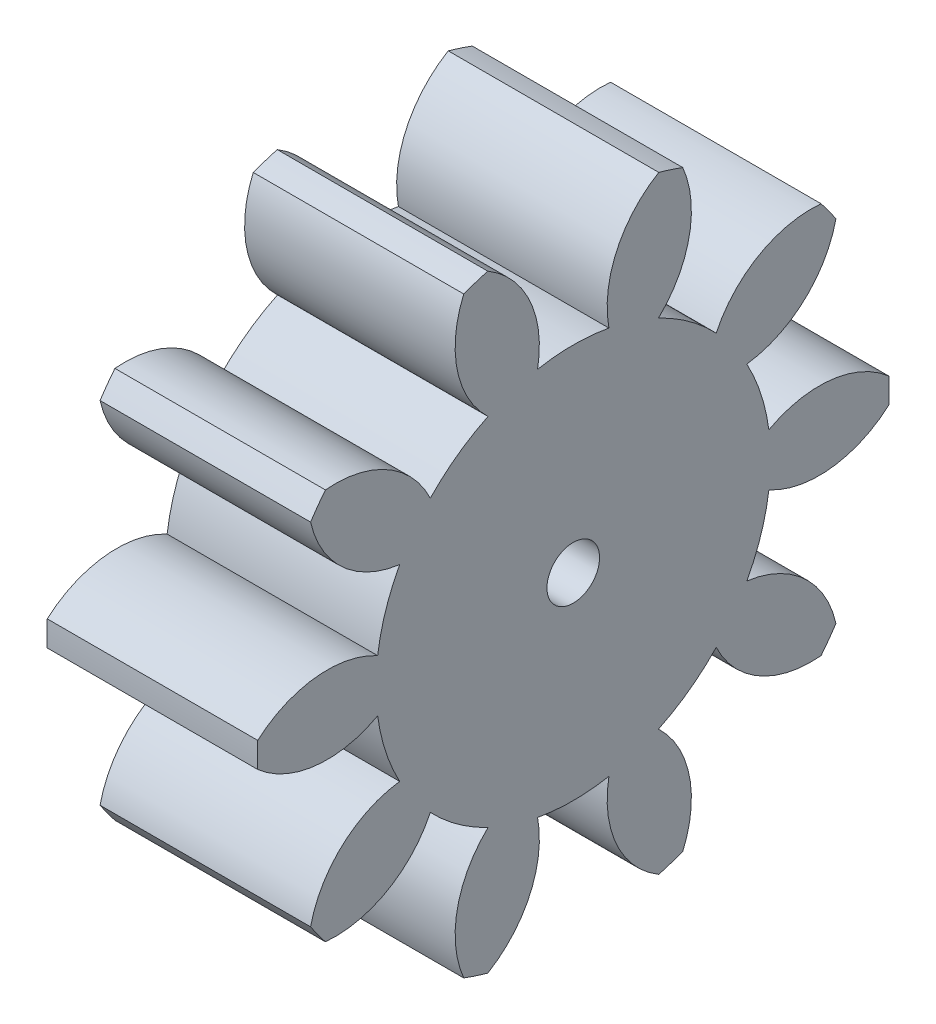
SolidWorks part; units mm, degrees
ref_plane "Plane1" through (0, 0, 0) normal (0, 0, 1) x (1, 0, 0)
ref_plane "Plane2" through (0, 0, 0) normal (0, 1, 0) x (1, 0, 0)
ref_plane "Plane3" through (0, 0, 0) normal (1, 0, 0) x (0, 0, -1)
sketch "HoldingSke" plane through (0, 0, 0) normal (0, 1, 0) x (1, 0, 0)
  line L0 (0, 0) -> (0.3283, -0.0579)
  line L1 (-15, 0) -> (100, 0) construction
  line L2 (0, 0) -> (-2.1039, 2.3779)
  line L3 (0, 0) -> (-11.863, 4.5341)
  line L4 (0, 0) -> (8.5048, 1.4996)
  line L5 (0, 0) -> (-46.8476, -17.4728)
  line L6 (0, 0) -> (-9.9476, -6.7116)
  line L7 (-2.1039, 2.3779) -> (8.6586, 51.2059)
  line L8 (-76.2, 54.61) -> (-75.7, 54.61)
  line L9 (-67.7845, 28.3722) -> (-49.3413, 33.142)
  line L10 (-76.2, 71.12) -> (104.1128, 71.12)
  line L11 (0, 0) -> (-12, 0)
  line L12 (-76.2, 101.6) -> (-76.093, 101.6)
  line L13 (24.9733, 27.94) -> (52.9518, 28.4284)
  line L14 (24.9733, 27.94) -> (24.9743, 27.94)
  line L15 (24.9733, 27.94) -> (100.4006, 29.5858)
  line L16 (-63.627, -3) -> (-12.827, -3)
  circle A0 centre (0, 0) radius 1.5
  circle A1 centre (0, 0) radius 11.249
  circle A2 centre (0, 0) radius 37.5
  circle A3 centre (0, 0) radius 1.5
  dimension "MHD" = 22.498
  dimension "Hub_dia" = 75
  dimension "Bore" = 3
  dimension "MBD" = 3
  dimension "Num_teeth" = 10
  dimension "Pitch" = 0.3333
  dimension "Overall_len" = 50
  dimension "Show_teeth" = 10
  dimension "Thickness" = 12
  dimension "OAL" = 50.0001
  dimension "T_dim" = 0.5
  dimension "Ap" = 14.5
  dimension "H" = 19.05
  dimension "Pitch_radius" = 180.3128
  dimension "Width" = 12
  dimension "Backlash" = 0.107
  dimension "Addendum_fac" = 1
  dimension "Dedendum_fac" = 1.25
  dimension "Clearance_fac" = 0.25
  dimension "Dedendum_add" = 0.001
  dimension "Module" = 3
sketch "BasProSke" plane through (0, 0, 0) normal (0, 1, 0) x (1, 0, 0)
  line L0 (-10, 0) -> (60, 0) construction
  line L1 (0, 0) -> (0, 18)
  line L2 (0, 0) -> (12, 0)
  line L3 (12, 0) -> (12, 18)
  line L4 (12, 18) -> (0, 18)
  dimension "Thickness" = 12
  dimension "Diameter" = 36
revolve "Base-Revolve" add sketch "BasProSke" angle 360 about L0
sketch "TooCutSke" plane through (0, 0, 0) normal (1, 0, 0) x (0, 0, -1)
  line L1 (0, 0) -> (0, 107) construction
  line L2 (0, 0) -> (-2.5334, 14.7845) construction
  line L3 (0, 0) -> (-9.174, 28.2345) construction
  line L4 (-2.5334, 14.7845) -> (-4.587, 14.1173) construction
  arc A0 (2.0333, 11.0637) -> (-2.0333, 11.0637) centre (0, 0) ccw
  arc A1 (4.9042, 17.3454) -> (-4.9042, 17.3454) centre (0, 0) ccw
  circle A2 centre (0, 0) radius 15 construction
  circle A3 centre (0, 0) radius 14.5222 construction
  arc A4 (-2.0333, 11.0637) -> (-4.9042, 17.3454) centre (-7.9314, 12.165) ccw
  arc A5 (4.9042, 17.3454) -> (2.0333, 11.0637) centre (7.9314, 12.165) ccw
  dimension "Root_dia" = 22.498
  dimension "Overcut_dia" = 36.0508
  dimension "Pitch_dia" = 30
  dimension "Base_dia" = 29.0444
  dimension "Flank_rad" = 6
  dimension "Half_ang" = 18
  dimension "Half_CT" = 2.1593
extrude "ToothCut" cut sketch "TooCutSke" along normal through all
fillet "Breaks" [suppressed] radius 0.06
fillet "RootFillets" [suppressed] radius 0.751
pattern_circular "TeethCuts" count 10 every 36 about axis through (-10, 0, 0) along (1, 0, 0) of "ToothCut", "RootFillets", "Breaks"
sketch "HubNeaOneSke" plane through (0, 0, 0) normal (-1, 0, 0) x (0, 0, 1)
  circle A0 centre (0, 0) radius 11.249
  dimension "Diameter" = 22.498
extrude "HubNearOne" [suppressed] add sketch "HubNeaOneSke" along normal blind 38.0001
sketch "HubNeaBotSke" plane through (0, 0, 0) normal (-1, 0, 0) x (0, 0, 1)
  circle A0 centre (0, 0) radius 11.249
  dimension "Diameter" = 22.498
extrude "HubNearBoth" [suppressed] add sketch "HubNeaBotSke" along normal blind 19
ref_plane "FarPln" through (12, 0, 0) normal (1, 0, 0) x (0, 0, -1)
sketch "HubFarSke" plane through (12, 0, 0) normal (1, 0, 0) x (0, 0, -1)
  circle A0 centre (0, 0) radius 11.249
  dimension "Diameter" = 22.498
extrude "HubFar" [suppressed] add sketch "HubFarSke" along normal blind 19
sketch "BorSke" plane through (0, 0, 0) normal (1, 0, 0) x (0, 0, -1)
  circle A0 centre (0, 0) radius 1.5
  dimension "Diameter" = 3
extrude "Bore" cut sketch "BorSke" along normal mid plane 100.0001
sketch "KeySke" plane through (0, 0, 0) normal (1, 0, 0) x (0, 0, -1)
  line L0 (-0.6, 0) -> (-0.6, 2)
  line L1 (-0.6, 2) -> (0.6, 2)
  line L2 (0.6, 2) -> (0.6, 0)
  line L3 (0, 0) -> (0, 34) construction
  line L4 (-0.6, 0) -> (0.6, 0)
  dimension "Offset" = 2
extrude "Keyway" [suppressed] cut sketch "KeySke" along normal mid plane 100.0001
pattern_circular "Keyway2" [suppressed] count 2 every 90 about axis through (-10, 0, 0) along (1, 0, 0)
equation "' \"Module@HoldingSke\" = 6.35"
equation "' \"Num_teeth@HoldingSke\" = 12"
equation "' \"Ap@HoldingSke\" =  20"
equation "' \"Ap@HoldingSke\" = 20"
equation "' \"Width@HoldingSke\" = 0.5 * 25.4"
equation "' \"Hub_dia@HoldingSke\"= 1 * 25.4"
equation "' \"Hub_dia@HoldingSke\" = 1 * 25.4"
equation "' \"Overall_len@HoldingSke\" = 1.0 * 25.4"
equation "' \"Bore@HoldingSke\" = 0.75 * 25.4"
equation "' \"T_dim@HoldingSke\" = 0.1 * 25.4"
equation "' \"Width@KeySke\" = 0.25 * 25.4"
equation "' \"Show_teeth@HoldingSke\" = 13"
equation "' \"Backlash@HoldingSke\" = 0.009 * 25.4"
equation "' \"Addendum_fac@HoldingSke\" = 1.0"
equation "' \"Dedendum_fac@HoldingSke\" = 1.25"
equation "' \"Dedendum_add@HoldingSke\" = 0.00005 * 25.4"
equation "' \"Clearance_fac@HoldingSke\" = 0.25"
equation "\"Pitch@HoldingSke\" = 1 / \"Module@HoldingSke\""
equation "\"Overcut_dia@TooCutSke\" = (\"Num_teeth@HoldingSke\" + 2 * \"Addendum_fac@HoldingSke\") / \"Pitch@HoldingSke\" + 0.002 * 25.4"
equation "\"Pitch_dia@TooCutSke\" = \"Num_teeth@HoldingSke\" / \"Pitch@HoldingSke\""
equation "\"Base_dia@TooCutSke\" = \"Num_teeth@HoldingSke\" / \"Pitch@HoldingSke\" * cos((\"Ap@HoldingSke\"  * 3.14159265 / 180))"
equation "\"Root_dia@TooCutSke\" = (\"Num_teeth@HoldingSke\" + 2) / \"Pitch@HoldingSke\" - 2 * (\"Addendum_fac@HoldingSke\" + \"Dedendum_fac@HoldingSke\") / \"Pitch@HoldingSke\" - \"Dedendum_add@HoldingSke\" * 2"
equation "\"Half_ang@TooCutSke\" = 180 / \"Num_teeth@HoldingSke\""
equation "\"Half_CT@TooCutSke\" = \"Num_teeth@HoldingSke\" / \"Pitch@HoldingSke\" * sin((3.14159265 / 2 / \"Num_teeth@HoldingSke\")) / 2 - 7 * \"Backlash@HoldingSke\" / 4"
equation "\"Flank_rad@TooCutSke\" = \"Num_teeth@HoldingSke\" / \"Pitch@HoldingSke\" / 5"
equation "\"Radius@RootFillets\" = \"Clearance_fac@HoldingSke\" / \"Pitch@HoldingSke\" + \"Dedendum_add@HoldingSke\""
equation "\"Break_rad@Breaks\" = 0.02 / \"Pitch@HoldingSke\""
equation "\"Thickness@HoldingSke\" = \"Width@HoldingSke\""
equation "\"OAL@HoldingSke\" = \"Thickness@HoldingSke\""
equation "\"MHD@HoldingSke\" = (\"Num_teeth@HoldingSke\" + 2) / \"Pitch@HoldingSke\" - 2 * (\"Addendum_fac@HoldingSke\" + \"Dedendum_fac@HoldingSke\")  / \"Pitch@HoldingSke\" - \"Dedendum_add@HoldingSke\" * 2"
equation "\"MBD@HoldingSke\" = (\"Num_teeth@HoldingSke\" + 2) / \"Pitch@HoldingSke\" - 2 * (\"Addendum_fac@HoldingSke\" + \"Dedendum_fac@HoldingSke\")  / \"Pitch@HoldingSke\" - \"Dedendum_add@HoldingSke\" * 2 - 0.002 * 25.4"
equation "\"MHD@HoldingSke\" = ((sgn( \"MHD@HoldingSke\" - \"Hub_dia@HoldingSke\" )-1)*( \"MHD@HoldingSke\" - \"Hub_dia@HoldingSke\" ))/-2+ \"Hub_dia@HoldingSke\""
equation "\"MBD@HoldingSke\" = ((sgn( \"MBD@HoldingSke\" - \"Bore@HoldingSke\" )-1)*( \"MBD@HoldingSke\" - \"Bore@HoldingSke\" ))/-2+ \"Bore@HoldingSke\""
equation "\"OAL@HoldingSke\" = ((sgn( \"OAL@HoldingSke\" - \"Overall_len@HoldingSke\" )+1)*( \"OAL@HoldingSke\" - \"Overall_len@HoldingSke\" ))/2 + \"Overall_len@HoldingSke\" + 0.000002 * 25.4"
equation "\"Num_teeth@TeethCuts\" = int( \"Show_teeth@HoldingSke\" ) + 1"
equation "\"Num_teeth@TeethCuts\" = ((sgn( \"Num_teeth@TeethCuts\" - \"Num_teeth@HoldingSke\" )-1)*( \"Num_teeth@TeethCuts\" - \"Num_teeth@HoldingSke\" ))/-2+ \"Num_teeth@HoldingSke\""
equation "\"Num_teeth@TeethCuts\" = ((sgn( \"Num_teeth@TeethCuts\" - 2.0)+1)*( \"Num_teeth@TeethCuts\" - 2.0))/2 +2.0"
equation "\"Angle@TeethCuts\" = 360.0 / \"Num_teeth@HoldingSke\""
equation "\"Diameter@BasProSke\" = (\"Num_teeth@HoldingSke\" + 2 * \"Addendum_fac@HoldingSke\") / \"Pitch@HoldingSke\""
equation "\"Thickness@BasProSke\"  = \"Thickness@HoldingSke\""
equation "' \"Fillet_rad@BasProSke\" =  \"Thickness@HoldingSke\" * 0.05"
equation "' \"Fillet_rad@BasProSke\" = \"Thickness@HoldingSke\" * 0.05"
equation "\"MHD@HoldingSke\" = ((sgn( \"MHD@HoldingSke\" - \"Root_dia@TooCutSke\" )-1)*( \"MHD@HoldingSke\" - \"Root_dia@TooCutSke\" ))/-2+ \"Root_dia@TooCutSke\""
equation "\"Diameter@HubNeaOneSke\" = \"MHD@HoldingSke\""
equation "\"Length@HubNearOne\" = \"OAL@HoldingSke\" - \"Thickness@BasProSke\""
equation "\"Diameter@HubNeaBotSke\" = \"MHD@HoldingSke\""
equation "\"Length@HubNearBoth\" = ( \"OAL@HoldingSke\" - \"Thickness@BasProSke\" ) / 2.0"
equation "\"Thickness@FarPln\" = \"Thickness@BasProSke\""
equation "\"Diameter@HubFarSke\" = \"MHD@HoldingSke\""
equation "\"Length@HubFar\" = ( \"OAL@HoldingSke\" - \"Thickness@BasProSke\" ) / 2.0"
equation "\"Diameter@BorSke\" = \"MBD@HoldingSke\""
equation "\"D1@Bore\" = \"OAL@HoldingSke\" * 2.0"
equation "\"D1@Keyway\" = \"OAL@HoldingSke\" * 2.0"
equation "\"Offset@KeySke\" = \"T_dim@HoldingSke\" + \"MBD@HoldingSke\" / 2.0"
